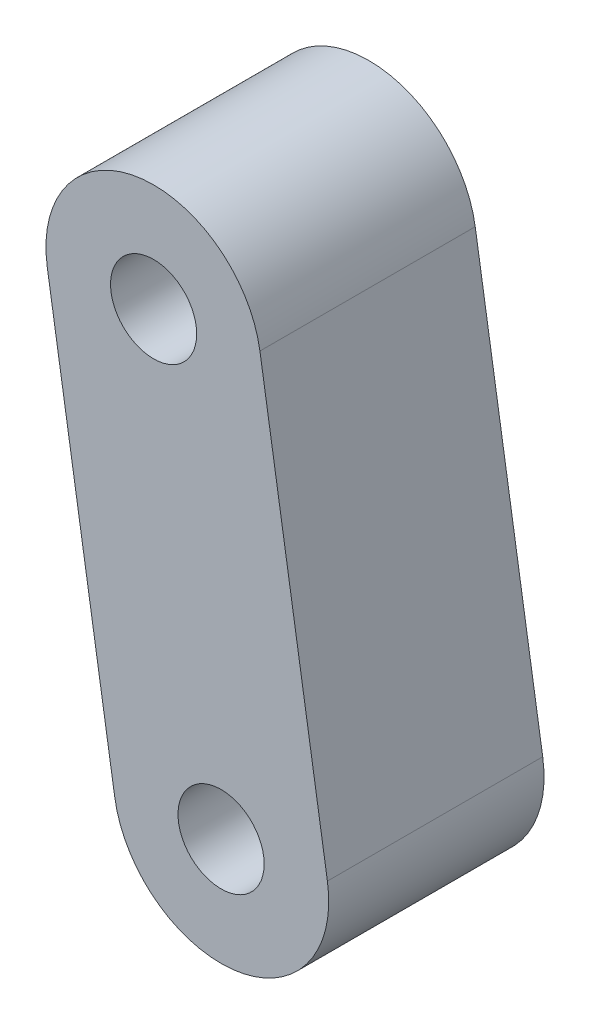
SolidWorks part; units mm, degrees
ref_plane "Front Plane" through (0, 0, 0) normal (0, 0, 1) x (1, 0, 0)
ref_plane "Top Plane" through (0, 0, 0) normal (0, 1, 0) x (1, 0, 0)
ref_plane "Right Plane" through (0, 0, 0) normal (1, 0, 0) x (0, 0, -1)
sketch "Sketch1" plane through (0, 0, 0) normal (0, 0, 1) x (1, 0, 0)
  line L42 (-64.0726, 14.9693) -> (-60.9382, -4.7836)
  line L43 (-54.1961, 16.5365) -> (-51.0618, -3.2164)
  arc A0 (-60.9382, -4.7836) -> (-51.0618, -3.2164) centre (-56, -4) ccw
  arc A1 (-54.1961, 16.5365) -> (-64.0726, 14.9693) centre (-59.1343, 15.7529) ccw
  circle A2 centre (-59.1343, 15.7529) radius 2
  circle A3 centre (-56, -4) radius 2
  dimension "D7" = 20
extrude "Boss-Extrude1" add sketch "Sketch1" along normal blind 10
